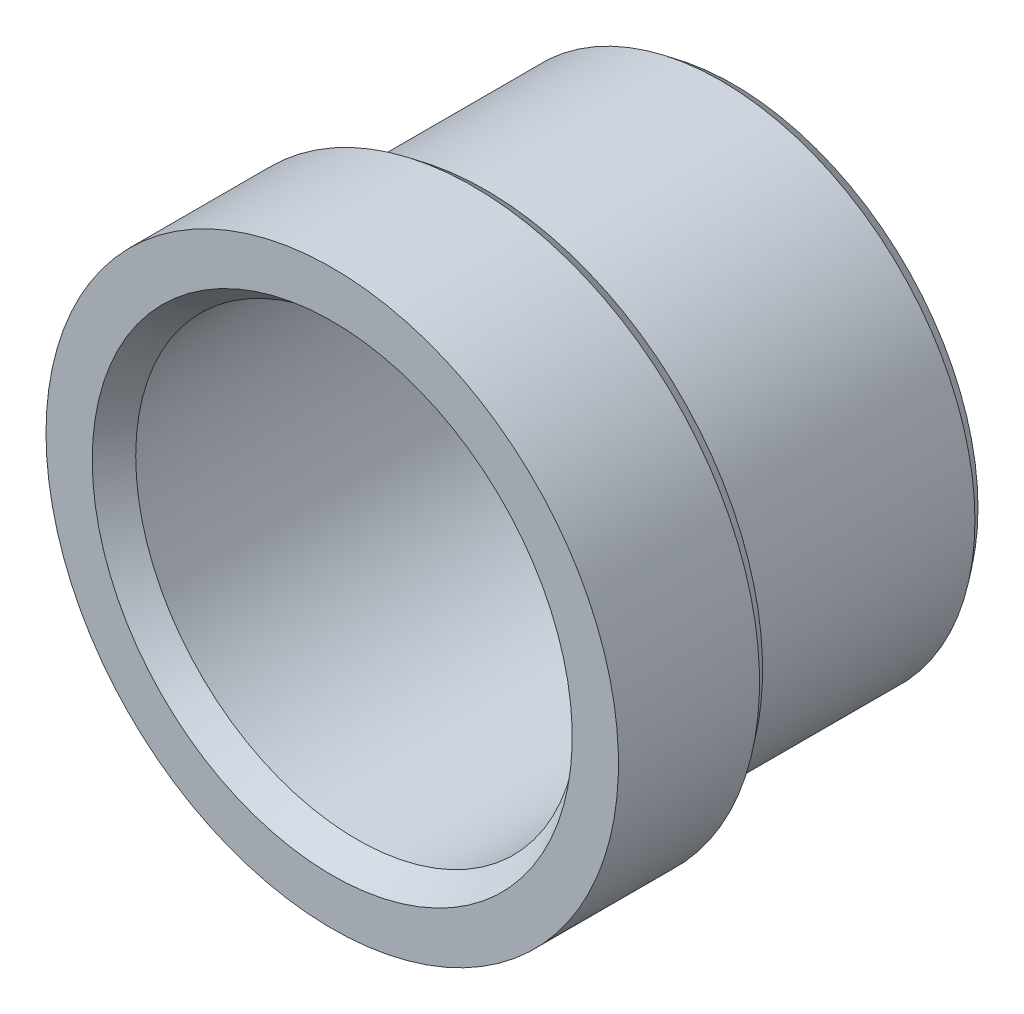
SolidWorks part; units mm, degrees
ref_plane "Front" through (0, 0, 0) normal (0, 0, 1) x (1, 0, 0)
ref_plane "Top" through (0, 0, 0) normal (0, 1, 0) x (1, 0, 0)
ref_plane "Right" through (0, 0, 0) normal (1, 0, 0) x (0, 0, -1)
sketch "Sketch1" plane through (0, 0, 0) normal (1, 0, 0) x (0, 0, -1)
  line L1 (8.636, 9.525) -> (8.636, 10.922)
  line L2 (8.636, 10.922) -> (-2.032, 10.922)
  line L3 (-2.032, 10.922) -> (-2.032, 12.319)
  line L4 (-2.032, 12.319) -> (-8.636, 12.319)
  line L5 (-8.636, 12.319) -> (-8.636, 10.3289)
  line L6 (-7.5692, 9.525) -> (8.636, 9.525)
  line L7 (8.636, 0) -> (-8.636, 0) construction
  line L8 (-8.636, 10.3289) -> (-7.5692, 9.525)
  point P0 (-8.636, 9.525)
  dimension "Length [L]" = 17.272
  dimension "Flange Length [L1]" = 6.604
  dimension "Flange OD [X]" = 24.638
  dimension "For Tube OD" = 19.05
  dimension "Flared Angle" = 37
  dimension "D1" = 1.0668
sketch "Sketch2" plane through (0, 0, 0) normal (1, 0, 0) x (0, 0, -1)
  line L0 (8.636, 9.525) -> (8.636, 10.922) construction
  line L1 (-7.5692, 9.525) -> (8.636, 9.525) construction
  line L2 (-8.636, 12.319) -> (-8.636, 10.3289) construction
  line L4 (-2.032, 12.319) -> (-8.636, 12.319) construction
  line L5 (-2.032, 10.922) -> (-2.032, 12.319) construction
  line L6 (8.636, 10.922) -> (-2.032, 10.922) construction
  line L7 (8.636, 9.525) -> (8.636, 10.922)
  line L8 (-7.5692, 9.525) -> (8.636, 9.525)
  line L11 (-2.032, 12.319) -> (-8.636, 12.319)
  line L12 (-2.032, 10.922) -> (-2.032, 12.319)
  line L13 (8.636, 10.922) -> (-2.032, 10.922)
  line L14 (-8.636, 10.3289) -> (-7.5692, 9.525) construction
  line L15 (-8.636, 12.319) -> (-8.636, 10.3289)
  line L16 (-8.636, 10.3289) -> (-7.5692, 9.525)
revolve "Revolve1" add sketch "Sketch2" angle 360 about L7
chamfer "Chamfer2" distance 0.5334 angle 37 2 edges at (-10.922, 0, -8.636) (-12.319, 0, 2.032)
equation "\"D1@Chamfer2\"=\"For Tube OD@Sketch1\"*.028"
equation "\"D1@Sketch1\"=\"For Tube OD@Sketch1\" * .056"
